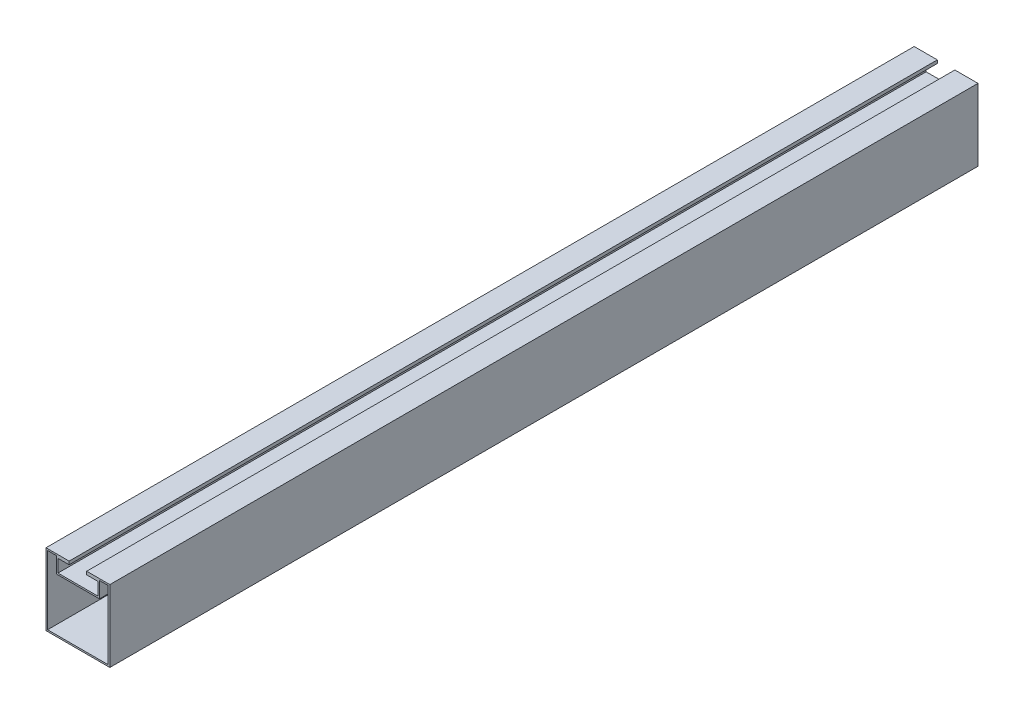
SolidWorks part; units mm, degrees
ref_plane "Front Plane" through (0, 0, 0) normal (0, 0, 1) x (1, 0, 0)
ref_plane "Top Plane" through (0, 0, 0) normal (0, 1, 0) x (1, 0, 0)
ref_plane "Right Plane" through (0, 0, 0) normal (1, 0, 0) x (0, 0, -1)
sketch "Sketch1" plane through (0, 0, 0) normal (0, 0, 1) x (1, 0, 0)
  line L0 (0, 45) -> (14.5, 45)
  line L1 (0, 0) -> (40, 0)
  line L2 (0, 0) -> (0, 45)
  line L3 (25.5, 45) -> (40, 45)
  line L4 (40, 0) -> (40, 45)
  line L5 (7.5, 43) -> (7.5, 35)
  line L6 (32.5, 43) -> (32.5, 35)
  line L8 (0, 45) -> (0, 44)
  line L9 (0, 45) -> (14.5, 45)
  line L10 (0, 45) -> (1, 45)
  line L12 (0, 0) -> (0, 1)
  line L14 (40, 0) -> (39, 0)
  line L23 (6.5, 34) -> (6.5, 44)
  line L25 (6.5, 44) -> (1, 44)
  line L29 (9.5953, 43) -> (7.5, 43)
  line L31 (7.5, 35) -> (32.5, 35)
  line L32 (6.5, 34) -> (33.5, 34)
  line L33 (1, 44) -> (1, 1)
  line L34 (1, 1) -> (39, 1)
  line L35 (39, 1) -> (39, 44)
  line L36 (39, 44) -> (33.5, 44)
  line L37 (33.5, 44) -> (33.5, 34)
  line L38 (14.5, 43) -> (14.5, 45)
  line L39 (14.5, 43) -> (9.5953, 43)
  line L40 (25.5, 43) -> (25.5, 45)
  line L41 (25.5, 43) -> (32.5, 43)
extrude "Boss-Extrude1" add sketch "Sketch1" along normal blind 550 contours L40 L41 L6 L31 L5 L29 L39 L38 L9 L0 L2 L1 L4 L3 L37 L36 L35 L34 L33 L25 L23 L32
sketch "Sketch2" plane through (0, 35, 0) normal (0, 1, 0) x (1, 0, 0)
  circle A0 centre (20, -40) radius 3
  circle A1 centre (20, -510) radius 3
  dimension "D1" = 6
extrude "Cut-Extrude2" cut sketch "Sketch2" against normal blind 200
sketch "Sketch3" plane through (0, 0, 0) normal (0, 0, -1) x (-1, 0, 0)
  line L1 (-42.6136, 46.7719) -> (4.6722, 46.7719)
  line L2 (-42.6136, 46.7719) -> (-42.6136, -7.9283)
  line L3 (-42.6136, -7.9283) -> (4.6722, -7.9283)
  line L4 (4.6722, 46.7719) -> (4.6722, -7.9283)
extrude "Cut-Extrude3" cut sketch "Sketch3" against normal blind 6
